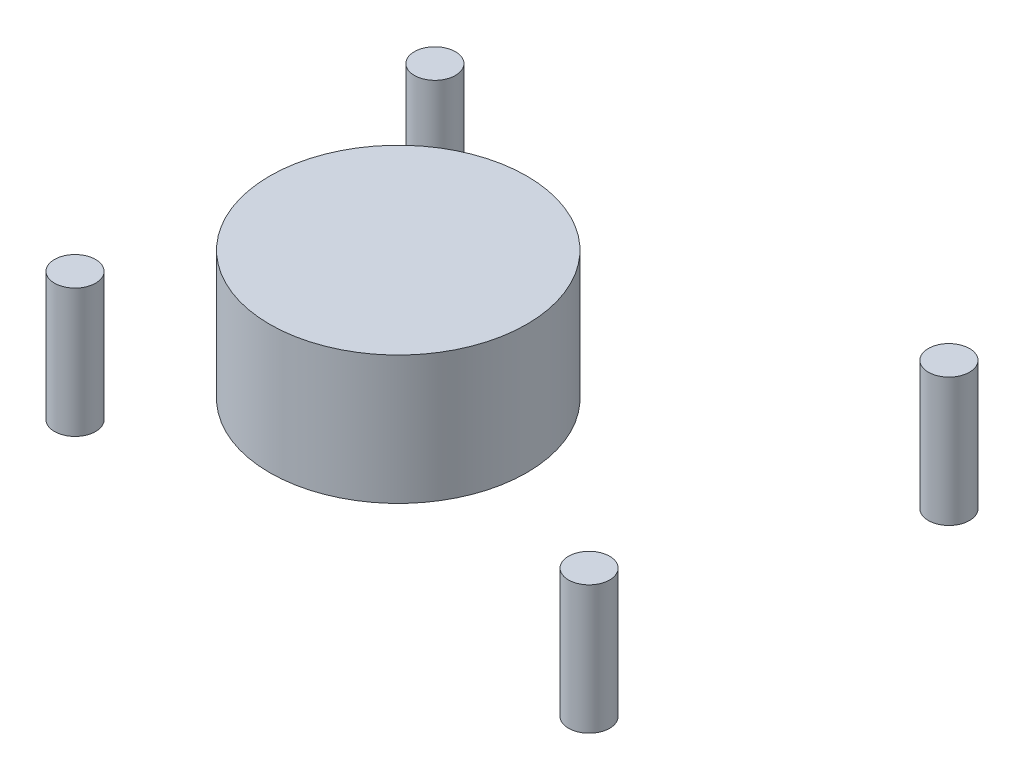
SolidWorks part; units mm, degrees
ref_plane "Front Plane" through (0, 0, 0) normal (0, 0, 1) x (1, 0, 0)
ref_plane "Top Plane" through (0, 0, 0) normal (0, 1, 0) x (1, 0, 0)
ref_plane "Right Plane" through (0, 0, 0) normal (1, 0, 0) x (0, 0, -1)
sketch "Sketch1" plane through (0, 0, 0) normal (0, 1, 0) x (1, 0, 0)
  line L0 (69.2296, 24.1084) -> (31.3296, 24.1084) construction
  line L5 (20.1796, 10.1084) -> (60.1796, 10.1084)
  line L6 (20.1796, 10.1084) -> (20.1796, 38.1084)
  line L7 (20.1796, 38.1084) -> (60.1796, 38.1084)
  line L8 (60.1796, 10.1084) -> (60.1796, 38.1084)
  line L9 (11.1296, 4.0584) -> (69.2296, 4.0584)
  line L10 (11.1296, 4.0584) -> (11.1296, 44.1584)
  line L11 (11.1296, 44.1584) -> (69.2296, 44.1584)
  line L12 (69.2296, 4.0584) -> (69.2296, 44.1584)
  circle A0 centre (20.1796, 38.1084) radius 1.6
  circle A1 centre (60.1796, 38.1084) radius 1.6
  circle A2 centre (20.1796, 10.1084) radius 1.6
  circle A3 centre (60.1796, 10.1084) radius 1.6
  circle A4 centre (31.3296, 24.1084) radius 10
  circle A5 centre (20.1796, 38.1084) radius 2
  circle A6 centre (60.1796, 38.1084) radius 2
  circle A7 centre (60.1796, 10.1084) radius 2
  circle A8 centre (20.1796, 10.1084) radius 2
  dimension "D5" = 3.2
  dimension "D6" = 3.2
  dimension "D7" = 3.2
  dimension "D8" = 3.2
  dimension "D9" = 9.05
  dimension "D14" = 20
  dimension "D15" = 4
  dimension "D16" = 4
  dimension "D17" = 4
  dimension "D18" = 4
  dimension "D1" = 40.1
  dimension "D2" = 58.1
  dimension "D3" = 28
  dimension "D4" = 40
  dimension "D10" = 9.05
  dimension "D11" = 6.05
  dimension "D12" = 6.05
  dimension "D13" = 37.9
extrude "Boss-Extrude1" add sketch "Sketch1" along normal blind 10 contours A0 | A2 | A4 | A1 | A3
